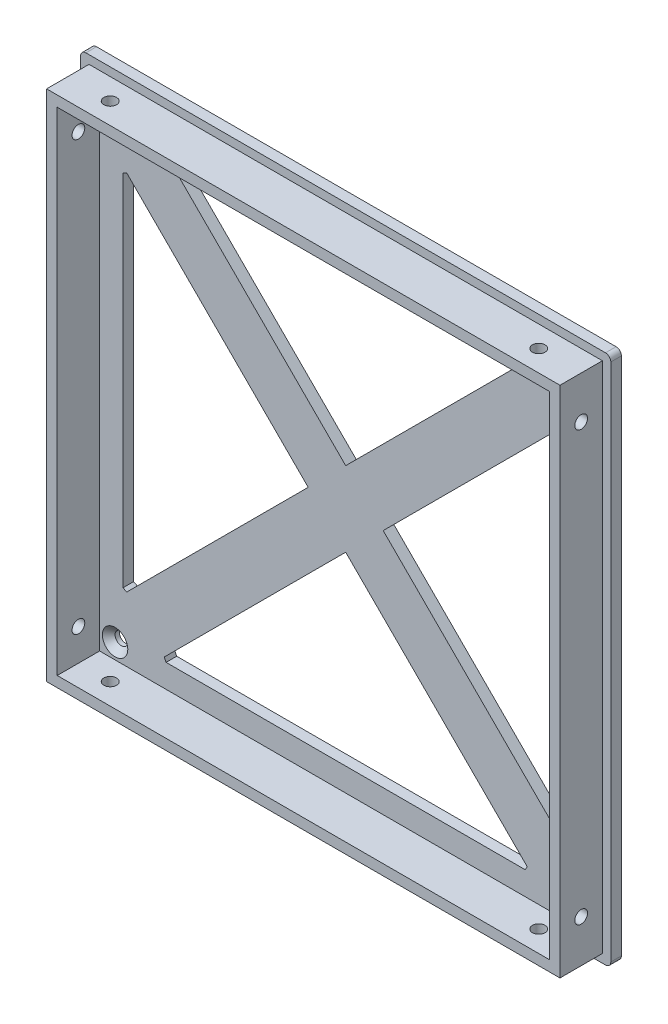
SolidWorks part; units mm, degrees
material "6061 Alloy"
ref_plane "Front Plane" through (0, 0, 0) normal (0, 0, 1) x (1, 0, 0)
ref_plane "Top Plane" through (0, 0, 0) normal (0, 1, 0) x (1, 0, 0)
ref_plane "Right Plane" through (0, 0, 0) normal (1, 0, 0) x (0, 0, -1)
sketch "Sketch1" plane through (0, 0, 0) normal (0, 0, 1) x (1, 0, 0)
  line L0 (0, 100) -> (100, 0) construction
  line L1 (0, 0) -> (100, 0)
  line L2 (0, 0) -> (0, 100)
  line L3 (0, 100) -> (100, 100)
  line L4 (100, 0) -> (100, 100)
  line L5 (0, 0) -> (100, 100) construction
  line L6 (8, 16.1245) -> (8, 83.8755)
  line L7 (8, 8) -> (92, 8) construction
  line L8 (8, 8) -> (8, 92) construction
  line L9 (8, 92) -> (92, 92) construction
  line L10 (92, 8) -> (92, 92) construction
  line L11 (8, 8) -> (92, 92) construction
  line L12 (8, 92) -> (92, 8) construction
  line L13 (16.1245, 92) -> (83.8755, 92)
  line L14 (92, 83.8755) -> (92, 16.1245)
  line L15 (16.1245, 8) -> (83.8755, 8)
  line L16 (8.6915, 84.2374) -> (42.9289, 50)
  line L17 (15.7626, 8.6915) -> (50, 42.9289)
  line L18 (15.7626, 91.3085) -> (50, 57.0711)
  line L19 (8.6915, 15.7626) -> (42.9289, 50)
  line L20 (-3.5355, 96.4645) -> (96.4645, -3.5355) construction
  line L21 (3.5355, 103.5355) -> (103.5355, 3.5355) construction
  line L22 (50, 42.9289) -> (84.2374, 8.6915)
  line L23 (-3.5355, 3.5355) -> (96.4645, 103.5355) construction
  line L24 (57.0711, 50) -> (91.3085, 84.2374)
  line L25 (3.5355, -3.5355) -> (103.5355, 96.4645) construction
  line L26 (57.0711, 50) -> (91.3085, 15.7626)
  line L27 (50, 57.0711) -> (84.2374, 91.3085)
  line L29 (1.5875, 1.5875) -> (98.4125, 1.5875) construction
  line L30 (1.5875, 1.5875) -> (1.5875, 98.4125) construction
  line L31 (1.5875, 98.4125) -> (98.4125, 98.4125) construction
  line L32 (98.4125, 1.5875) -> (98.4125, 98.4125) construction
  line L33 (1.5875, 1.5875) -> (98.4125, 98.4125) construction
  line L34 (1.5875, 98.4125) -> (98.4125, 1.5875) construction
  line L35 (3.5875, 3.5875) -> (96.4125, 3.5875) construction
  line L36 (3.5875, 3.5875) -> (3.5875, 96.4125) construction
  line L37 (3.5875, 96.4125) -> (96.4125, 96.4125) construction
  line L38 (96.4125, 3.5875) -> (96.4125, 96.4125) construction
  line L39 (3.5875, 3.5875) -> (96.4125, 96.4125) construction
  line L40 (3.5875, 96.4125) -> (96.4125, 3.5875) construction
  arc A0 (8, 83.8755) -> (8.6915, 84.2374) centre (0, 100) ccw
  arc A1 (83.8755, 92) -> (84.2374, 91.3085) centre (100, 100) ccw
  arc A2 (92, 16.1245) -> (91.3085, 15.7626) centre (100, 0) ccw
  arc A3 (16.1245, 8) -> (15.7626, 8.6915) centre (0, 0) ccw
  arc A4 (8.6915, 15.7626) -> (8, 16.1245) centre (0, 0) ccw
  arc A5 (84.2374, 8.6915) -> (83.8755, 8) centre (100, 0) ccw
  arc A6 (91.3085, 84.2374) -> (92, 83.8755) centre (100, 100) ccw
  arc A7 (15.7626, 91.3085) -> (16.1245, 92) centre (0, 100) ccw
  circle A8 centre (5.7875, 94.2125) radius 2.2 construction
  point P9 (50, 50)
  point P34 (50, 50)
  point P43 (50, 50)
  dimension "D2" = 8
  dimension "D3" = 36
  dimension "D8" = 4.4
  dimension "D1" = 100
  dimension "D4" = 5
  dimension "D6" = 1.5875
  dimension "D7" = 2
  dimension "D5" = 5
extrude "Boss-Extrude1" add sketch "Sketch1" along normal blind 2
sketch "Sketch2" plane through (0, 0, 2) normal (0, 0, 1) x (1, 0, 0)
  line L0 (100, 0) -> (100, 100) construction
  line L1 (1.5875, 1.5875) -> (98.4125, 1.5875)
  line L2 (1.5875, 1.5875) -> (1.5875, 98.4125)
  line L3 (1.5875, 98.4125) -> (98.4125, 98.4125)
  line L4 (98.4125, 1.5875) -> (98.4125, 98.4125)
  line L5 (1.5875, 1.5875) -> (98.4125, 98.4125) construction
  line L6 (1.5875, 98.4125) -> (98.4125, 1.5875) construction
  line L7 (0, 0) -> (100, 0) construction
  line L8 (100, 100) -> (0, 100) construction
  line L9 (0, 100) -> (0, 0) construction
  line L10 (100, 0) -> (100, 100) construction
  line L11 (0, 0) -> (100, 0) construction
  line L12 (100, 100) -> (0, 100) construction
  line L13 (0, 100) -> (0, 0) construction
  line L14 (0, 100) -> (100, 0) construction
  line L15 (0, 0) -> (100, 100) construction
  line L17 (3.5875, 3.5875) -> (96.4125, 3.5875)
  line L18 (3.5875, 3.5875) -> (3.5875, 96.4125)
  line L19 (3.5875, 96.4125) -> (96.4125, 96.4125)
  line L20 (96.4125, 3.5875) -> (96.4125, 96.4125)
  line L21 (3.5875, 3.5875) -> (96.4125, 96.4125) construction
  line L22 (3.5875, 96.4125) -> (96.4125, 3.5875) construction
  point P0 (50, 50)
  point P10 (50, 50)
  point P12 (50, 50)
  dimension "D1" = 1.5875
  dimension "D2" = 2
extrude "Boss-Extrude2" add sketch "Sketch2" along normal blind 8
hole_wizard "CSK for M2 Flat Head Machine Screw1" positions "Sketch4" profile "Sketch5" countersink size "M2" standard "ANSI Metric"
sketch "Sketch4" plane through (0, 0, 2) normal (0, 0, 1) x (1, 0, 0)
  line L0 (0, 100) -> (100, 0) construction
  line L1 (0, 0) -> (100, 100) construction
  line L3 (6.5, 93.5) -> (93.5, 93.5) construction
  line L4 (6.5, 93.5) -> (6.5, 6.5) construction
  line L5 (6.5, 6.5) -> (93.5, 6.5) construction
  line L6 (93.5, 93.5) -> (93.5, 6.5) construction
  line L8 (0, 0) -> (100, 0) construction
  point P0 (6.5, 93.5)
  point P4 (93.5, 93.5)
  point P8 (93.5, 6.5)
  point P10 (6.5, 6.5)
  dimension "D1" = 6.5
sketch "Sketch5" plane through (6.5, 93.5, 2) normal (1, 0, 0) x (0, -1, 0)
  line L0 (0, 0) -> (0, 312.221)
  line L1 (0, 312.221) -> (1.2, 311.5)
  line L2 (1.2, 311.5) -> (1.2, 1.2)
  line L3 (1.2, 1.2) -> (2.4, 0)
  line L5 (2.4, 0) -> (0, 0)
  line L6 (-1.2, 1.2) -> (-2.4, 0) construction
  line L10 (0, 312.221) -> (-1.2, 311.5) construction
  line L11 (0, -6.35) -> (0, 107.95) construction
  dimension "Hole Dia." = 2.4
  dimension "Hole Depth" = 311.5
  dimension "Near C'Sink Dia." = 4.8
  dimension "Near C'Sink Angle" = 90
  dimension "Drill Angle" = 118
fillet "Fillet1" radius 1 4 edges at (0, 0, 1) (100, 0, 1) (100, 100, 1) (0, 100, 1)
hole_wizard "M2 Clearance Hole1" positions "Sketch6" profile "Sketch7" hole size "M2" standard "ANSI Metric" end condition through all
sketch "Sketch6" plane through (1.5875, 0, 0) normal (-1, 0, 0) x (0, 0, 1)
  line L0 (10, 98.4125) -> (10, 1.5875) construction
  line L1 (10, 98.4125) -> (2, 98.4125) construction
  line L2 (10, 1.5875) -> (2, 1.5875) construction
  point P0 (6, 90.4125)
  point P2 (6, 9.5875)
  dimension "D1" = 4
  dimension "D2" = 4
  dimension "D3" = 8
  dimension "D4" = 8
sketch "Sketch7" plane through (1.5875, 90.4125, 6) normal (0, 1, 0) x (0, 0, 1)
  line L0 (0, 0) -> (0, 98.4125)
  line L1 (0, 98.4125) -> (1.2, 98.4125)
  line L2 (1.2, 98.4125) -> (1.2, 0)
  line L5 (1.2, 0) -> (0, 0)
  line L11 (0, -6.35) -> (0, 107.95) construction
  dimension "Thru Hole Dia." = 2.4
  dimension "Thru Hole Depth" = 98.4125
hole_wizard "M2 Clearance Hole2" positions "Sketch8" profile "Sketch10" hole size "M2" standard "ANSI Metric" end condition through all
sketch "Sketch8" plane through (0, 98.4125, 0) normal (0, 1, 0) x (1, 0, 0)
  line L0 (98.4125, -10) -> (1.5875, -10) construction
  line L1 (1.5875, -10) -> (1.5875, -2) construction
  line L2 (98.4125, -10) -> (98.4125, -2) construction
  point P0 (9.5875, -6)
  point P2 (90.4125, -6)
  dimension "D1" = 4
  dimension "D2" = 8
  dimension "D3" = 8
  dimension "D4" = 4
sketch "Sketch10" plane through (9.5875, 98.4125, 6) normal (1, 0, 0) x (0, 0, 1)
  line L0 (0, 0) -> (0, 98.4125)
  line L1 (0, 98.4125) -> (1.2, 98.4125)
  line L2 (1.2, 98.4125) -> (1.2, 0)
  line L5 (1.2, 0) -> (0, 0)
  line L11 (0, -6.35) -> (0, 107.95) construction
  dimension "Thru Hole Dia." = 2.4
  dimension "Thru Hole Depth" = 98.4125
